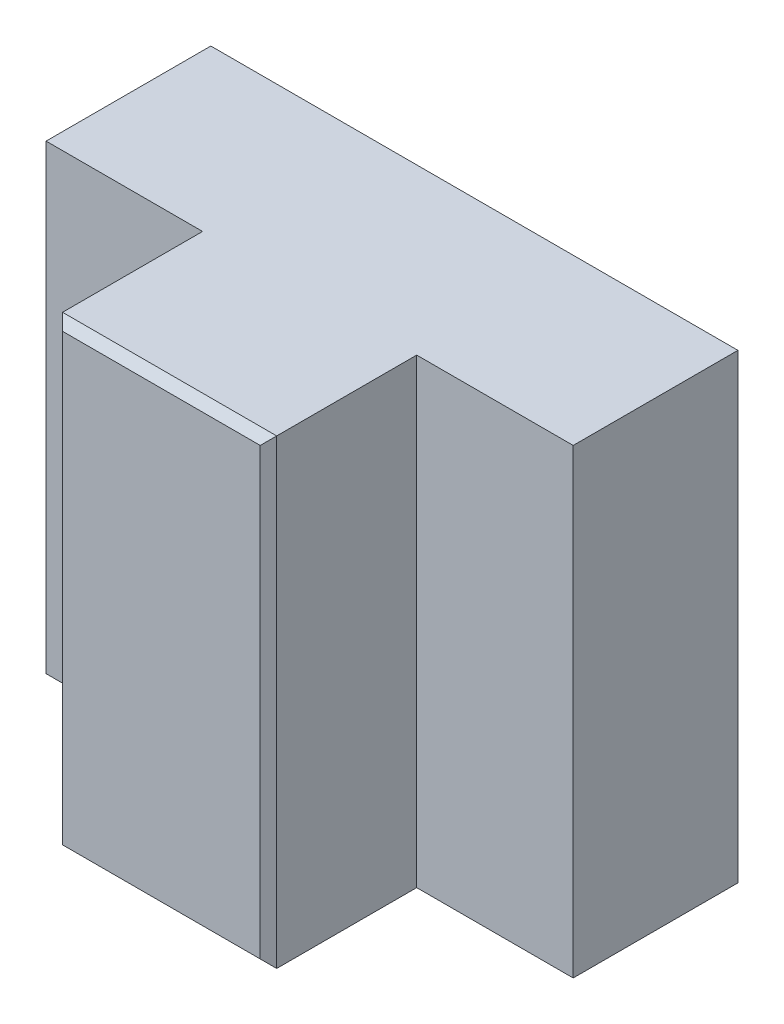
SolidWorks part; units mm, degrees
ref_plane "前视基准面" through (0, 0, 0) normal (0, 0, 1) x (1, 0, 0)
ref_plane "上视基准面" through (0, 0, 0) normal (0, 1, 0) x (1, 0, 0)
ref_plane "右视基准面" through (0, 0, 0) normal (1, 0, 0) x (0, 0, -1)
sketch "草图5" plane through (0, 0, 0) normal (0, 0, 1) x (1, 0, 0)
  line L1 (-16, 14) -> (16, 14)
  line L2 (-16, 14) -> (-16, -14)
  line L3 (-16, -14) -> (16, -14)
  line L4 (16, 14) -> (16, -14)
  line L5 (0, -14) -> (0, 14) construction
  line L6 (-16, 0) -> (16, 0) construction
  point P0 (0, 0)
  dimension "D1" = 28
  dimension "D2" = 32
extrude "凸台-拉伸5" add sketch "草图5" along normal blind 10
sketch "草图6" plane through (0, 0, 10) normal (0, 0, 1) x (1, 0, 0)
  line L0 (0, 14) -> (6.5, 14)
  line L1 (16, 14) -> (-16, 14) construction
  line L2 (6.5, 14) -> (6.5, -14)
  line L3 (-16, -14) -> (16, -14) construction
  line L4 (6.5, -14) -> (-6.5, -14)
  line L5 (-6.5, -14) -> (-6.5, 14)
  line L6 (-6.5, 14) -> (0, 14)
extrude "凸台-拉伸6" add sketch "草图6" along normal blind 9
chamfer "倒角4" distance 0.5 angle 45 4 edges at (6.5, 0, 19) (0, -14, 19) (-6.5, 0, 19) (0, 14, 19)
